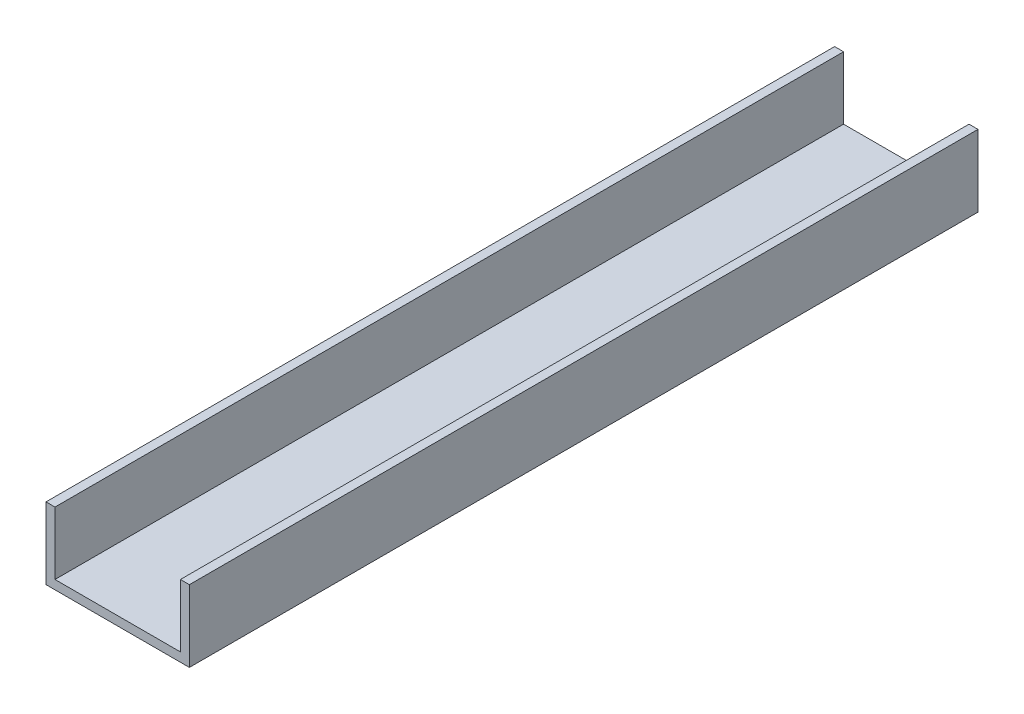
SolidWorks part; units mm, degrees
ref_plane "Front Plane" through (0, 0, 0) normal (0, 0, 1) x (1, 0, 0)
ref_plane "Top Plane" through (0, 0, 0) normal (0, 1, 0) x (1, 0, 0)
ref_plane "Right Plane" through (0, 0, 0) normal (1, 0, 0) x (0, 0, -1)
sketch "Sketch1" plane through (0, 0, 0) normal (0, 0, 1) x (1, 0, 0)
  line L0 (3.175, 3.175) -> (3.175, 25.4)
  line L1 (0, 0) -> (50.8, 0)
  line L2 (0, 0) -> (0, 25.4)
  line L3 (0, 25.4) -> (3.175, 25.4)
  line L4 (50.8, 0) -> (50.8, 25.4)
  line L5 (0, 0) -> (50.8, 25.4) construction
  line L6 (0, 25.4) -> (50.8, 0) construction
  line L7 (3.175, 3.175) -> (3.175, 22.225) construction
  line L8 (47.625, 3.175) -> (47.625, 25.4)
  line L9 (3.175, 3.175) -> (47.625, 3.175)
  line L10 (3.175, 22.225) -> (47.625, 22.225) construction
  line L11 (47.625, 3.175) -> (47.625, 22.225) construction
  line L12 (47.625, 25.4) -> (50.8, 25.4)
  line L13 (0, 25.4) -> (50.8, 25.4) construction
  point P4 (25.4, 12.7)
  dimension "D1" = 25.4
  dimension "D2" = 50.8
  dimension "D3" = 3.175
extrude "Boss-Extrude1" add sketch "Sketch1" along normal blind 279.4
